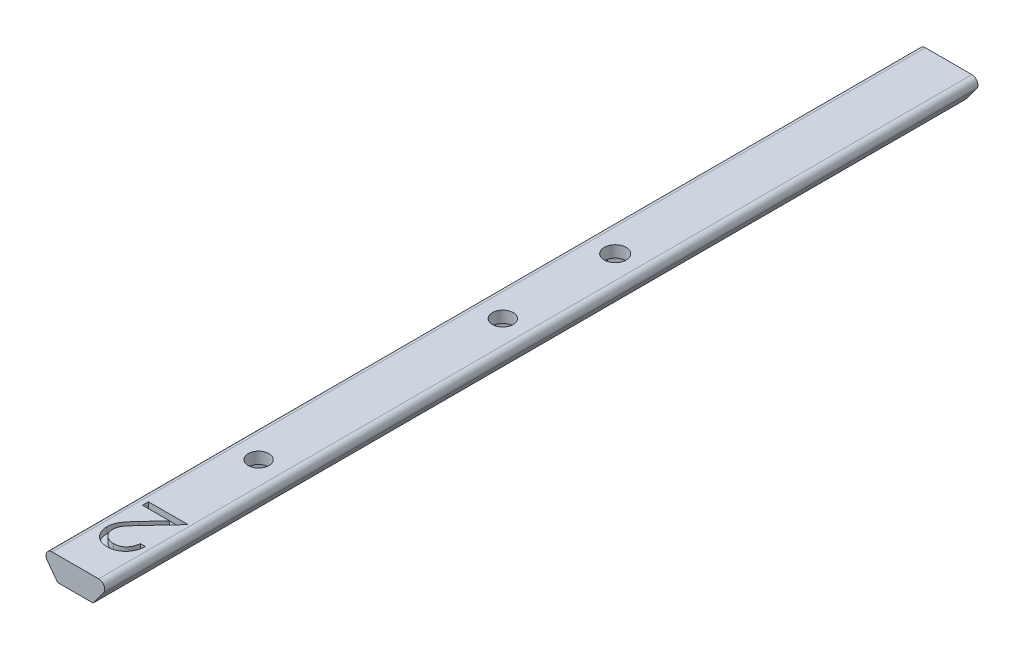
SolidWorks part; units mm, degrees
ref_plane "Front Plane" through (0, 0, 0) normal (0, 0, 1) x (1, 0, 0)
ref_plane "Top Plane" through (0, 0, 0) normal (0, 1, 0) x (1, 0, 0)
ref_plane "Right Plane" through (0, 0, 0) normal (1, 0, 0) x (0, 0, -1)
sketch "Sketch1" plane through (0, 0, 0) normal (0, 0, 1) x (1, 0, 0)
  line L0 (0, 0) -> (5.8, 0)
  line L1 (-2.9, 3.9) -> (8.7, 3.9)
  line L2 (0, 0) -> (-2.9, 3.9)
  line L3 (5.8, 0) -> (8.7, 3.9)
  dimension "D1" = 11.6
  dimension "D2" = 3.9
  dimension "D3" = 5.8
  dimension "D4" = 2.9
extrude "Boss-Extrude1" add sketch "Sketch1" along normal blind 143
fillet "Fillet1" radius 1 2 edges at (-2.9, 3.9, 71.5) (8.7, 3.9, 71.5)
sketch "Sketch2" plane through (0, 0, 0) normal (0, -1, 0) x (1, 0, 0)
  line L0 (2.9, 143) -> (2.9, 54.6) construction
  line L1 (0, 143) -> (5.8, 143) construction
  circle A0 centre (2.9, 54.6) radius 1.8
  dimension "D2" = 3.6
  dimension "D1" = 88.4
extrude "Cut-Extrude1" cut sketch "Sketch2" against normal blind 200
sketch "Sketch3" plane through (0, 0, 0) normal (0, -1, 0) x (1, 0, 0)
  line L1 (2.9, 57.9486) -> (0, 56.2743)
  line L2 (0, 56.2743) -> (0, 52.9257)
  line L3 (0, 52.9257) -> (2.9, 51.2514)
  line L4 (2.9, 51.2514) -> (5.8, 52.9257)
  line L5 (5.8, 52.9257) -> (5.8, 56.2743)
  line L6 (5.8, 56.2743) -> (2.9, 57.9486)
  circle A0 centre (2.9, 54.6) radius 2.9 construction
  dimension "D1" = 5.8
extrude "Cut-Extrude2" cut sketch "Sketch3" against normal blind 2
sketch "Sketch4" plane through (0, 3.9, 0) normal (0, 1, 0) x (1, 0, 0)
  line L0 (6.7102, -128) -> (4.7102, -128) construction
  line L2 (6.7102, -143) -> (-0.9102, -143) construction
  text T0 "2\r\n" font "Century Gothic" height in points 36
  dimension "D1" = 15
extrude "Cut-Extrude3" cut sketch "Sketch4" against normal blind 1
sketch "Sketch5" plane through (0, 3.9, 0) normal (0, 1, 0) x (1, 0, 0)
  line L0 (2.9, -143) -> (2.9, -113) construction
  line L1 (6.7102, -143) -> (-0.9102, -143) construction
  circle A0 centre (2.9, -113) radius 1.7
  dimension "D2" = 3.4
  dimension "D1" = 30
extrude "Cut-Extrude4" cut sketch "Sketch5" against normal blind 10
pattern_linear "LPattern1" count 2 spacing 40 along (0, 0, -1) of "Cut-Extrude4"
sketch "Sketch6" plane through (0, 0, 0) normal (0, -1, 0) x (1, 0, 0)
  line L0 (5.7971, 114.6794) -> (2.8942, 116.3486)
  line L1 (5.7971, 74.6794) -> (2.8942, 76.3486)
  line L2 (2.8942, 76.3486) -> (-0.0029, 74.6693)
  line L3 (-0.0029, 74.6693) -> (0.0029, 71.3206)
  line L4 (0.0029, 71.3206) -> (2.9058, 69.6514)
  line L5 (2.9058, 69.6514) -> (5.8029, 71.3307)
  line L6 (5.8029, 71.3307) -> (5.7971, 74.6794)
  line L7 (2.8942, 116.3486) -> (-0.0029, 114.6693)
  line L8 (-0.0029, 114.6693) -> (0.0029, 111.3206)
  line L9 (0.0029, 111.3206) -> (2.9058, 109.6514)
  line L10 (2.9058, 109.6514) -> (5.8029, 111.3307)
  line L11 (5.8029, 111.3307) -> (5.7971, 114.6794)
  circle A0 centre (2.9, 73) radius 2.9 construction
  circle A1 centre (2.9, 113) radius 2.9 construction
  dimension "D1" = 5.8
  dimension "D2" = 2
extrude "Cut-Extrude5" cut sketch "Sketch6" against normal up to vertex (2 mm away)
